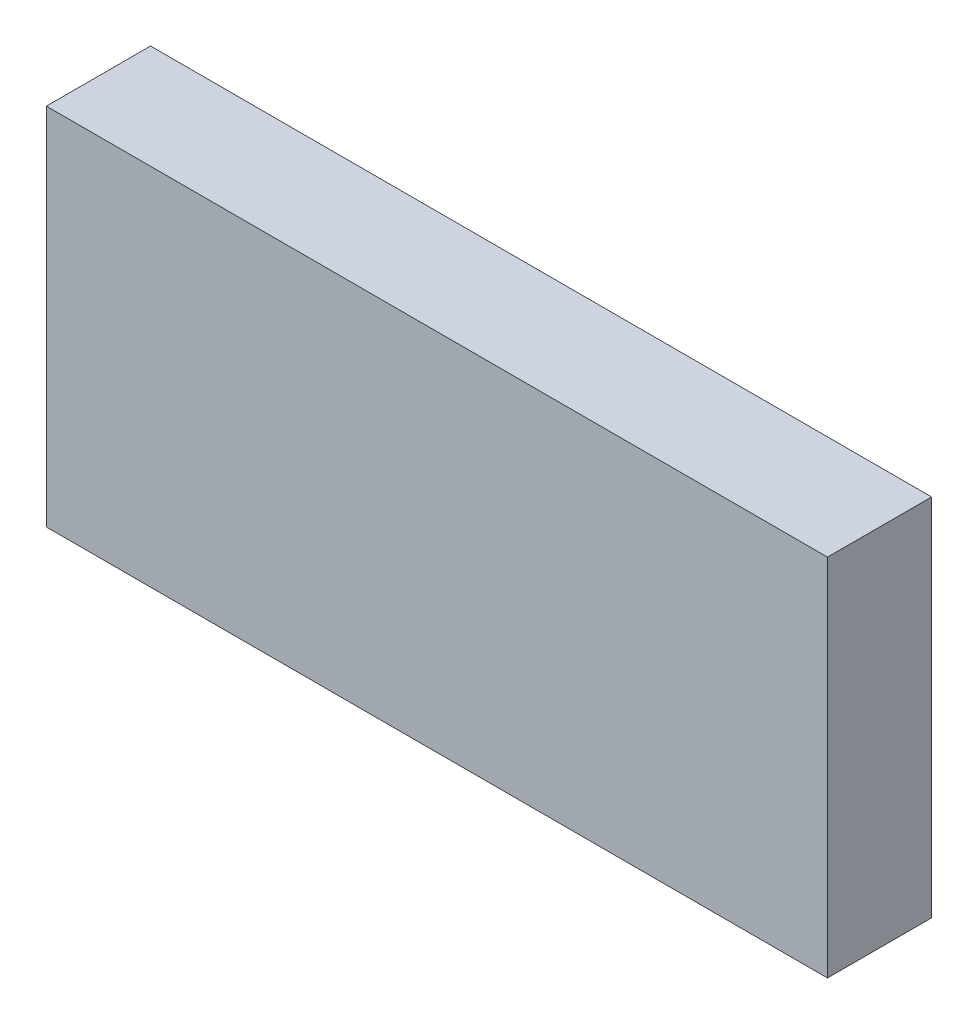
SolidWorks part; units mm, degrees
ref_plane "前视基准面" through (0, 0, 0) normal (0, 0, 1) x (1, 0, 0)
ref_plane "上视基准面" through (0, 0, 0) normal (0, 1, 0) x (1, 0, 0)
ref_plane "右视基准面" through (0, 0, 0) normal (1, 0, 0) x (0, 0, -1)
other "Configuration Table"
sketch "草图1" plane through (0, 0, 0) normal (0, 0, 1) x (1, 0, 0)
  line L1 (-75, -35) -> (75, -35)
  line L2 (-75, -35) -> (-75, 35)
  line L3 (-75, 35) -> (75, 35)
  line L4 (75, -35) -> (75, 35)
  line L5 (-75, -35) -> (75, 35) construction
  line L6 (-75, 35) -> (75, -35) construction
  point P0 (0, 0)
extrude "凸台-拉伸1" add sketch "草图1" along normal blind 20
